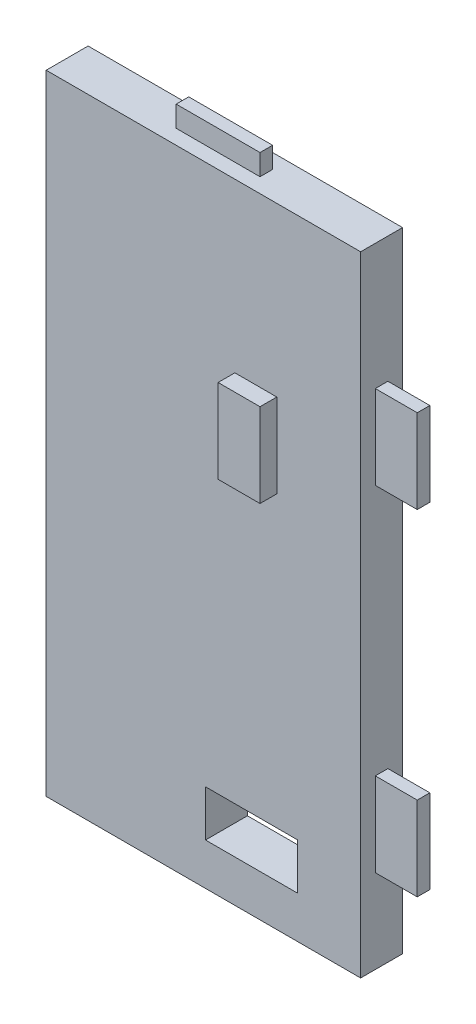
SolidWorks part; units mm, degrees
ref_plane "Front Plane" through (0, 0, 0) normal (1, 0, 0) x (0, 1, 0)
ref_plane "Top Plane" through (0, 0, 0) normal (0, 0, 1) x (0, 1, 0)
ref_plane "Right Plane" through (0, 0, 0) normal (0, 1, 0) x (-1, 0, 0)
sketch "Sketch1" plane through (0, 0, 0) normal (0, 0, 1) x (0, 1, 0)
  line L1 (-75, -37.5) -> (75, -37.5)
  line L2 (-75, -37.5) -> (-75, 37.5)
  line L3 (-75, 37.5) -> (75, 37.5)
  line L4 (75, -37.5) -> (75, 37.5)
  line L5 (-75, -37.5) -> (75, 37.5) construction
  line L6 (-75, 37.5) -> (75, -37.5) construction
  line L7 (-65, -22.5) -> (-54, -22.5)
  line L8 (-65, -22.5) -> (-65, -0.5)
  line L9 (-65, -0.5) -> (-54, -0.5)
  line L10 (-54, -22.5) -> (-54, -0.5)
  line L11 (-65, -22.5) -> (-54, -0.5) construction
  line L12 (-65, -0.5) -> (-54, -22.5) construction
  point P0 (0, 0)
  point P6 (-59.5, -11.5)
  dimension "D1" = 150
  dimension "D2" = 75
  dimension "D3" = 26
  dimension "D4" = 22
  dimension "D5" = 11
  dimension "D6" = 10
extrude "Boss-Extrude1" add sketch "Sketch1" along normal blind 10
sketch "Sketch2" plane through (0, 0, 10) normal (0, 0, 1) x (1, 0, 0)
  line L1 (7.5, 15) -> (17.5, 15)
  line L2 (7.5, 15) -> (7.5, 35)
  line L3 (7.5, 35) -> (17.5, 35)
  line L4 (17.5, 15) -> (17.5, 35)
  line L5 (7.5, 15) -> (17.5, 35) construction
  line L6 (7.5, 35) -> (17.5, 15) construction
  line L7 (37.5, -75) -> (37.5, 75) construction
  line L8 (37.5, 75) -> (-37.5, 75) construction
  point P0 (12.5, 25)
  dimension "D1" = 60
  dimension "D2" = 10
  dimension "D3" = 20
  dimension "D4" = 25
extrude "Boss-Extrude2" add sketch "Sketch2" along normal blind 4
sketch "Sketch3" plane through (37.5, 0, 0) normal (1, 0, 0) x (0, 1, 0)
  line L0 (-75, 0) -> (75, 0) construction
  line L1 (-55, 3.5) -> (-35, 3.5)
  line L2 (-55, 3.5) -> (-55, 6.5)
  line L3 (-55, 6.5) -> (-35, 6.5)
  line L4 (-35, 3.5) -> (-35, 6.5)
  line L5 (-55, 3.5) -> (-35, 6.5) construction
  line L6 (-55, 6.5) -> (-35, 3.5) construction
  line L7 (25, 3.5) -> (45, 3.5)
  line L8 (25, 3.5) -> (25, 6.5)
  line L9 (25, 6.5) -> (45, 6.5)
  line L10 (45, 3.5) -> (45, 6.5)
  line L11 (25, 3.5) -> (45, 6.5) construction
  line L12 (25, 6.5) -> (45, 3.5) construction
  line L14 (75, 10) -> (75, 0) construction
  point P0 (-45, 5)
  point P5 (35, 5)
  point P14 (45, 5)
  dimension "D1" = 5
  dimension "D2" = 3
  dimension "D3" = 20
  dimension "D4" = 5
  dimension "D5" = 3
  dimension "D6" = 20
  dimension "D7" = 80
  dimension "D8" = 30
extrude "Boss-Extrude3" add sketch "Sketch3" along normal blind 10
sketch "Sketch4" plane through (0, 75, 0) normal (0, 1, 0) x (-1, 0, 0)
  line L0 (-37.5, 0) -> (37.5, 0) construction
  line L1 (-10, 3.5) -> (10, 3.5)
  line L2 (-10, 3.5) -> (-10, 6.5)
  line L3 (-10, 6.5) -> (10, 6.5)
  line L4 (10, 3.5) -> (10, 6.5)
  line L5 (-10, 3.5) -> (10, 6.5) construction
  line L6 (-10, 6.5) -> (10, 3.5) construction
  point P0 (0, 5)
  dimension "D1" = 5
  dimension "D2" = 3
  dimension "D3" = 20
extrude "Boss-Extrude4" add sketch "Sketch4" along normal blind 5
